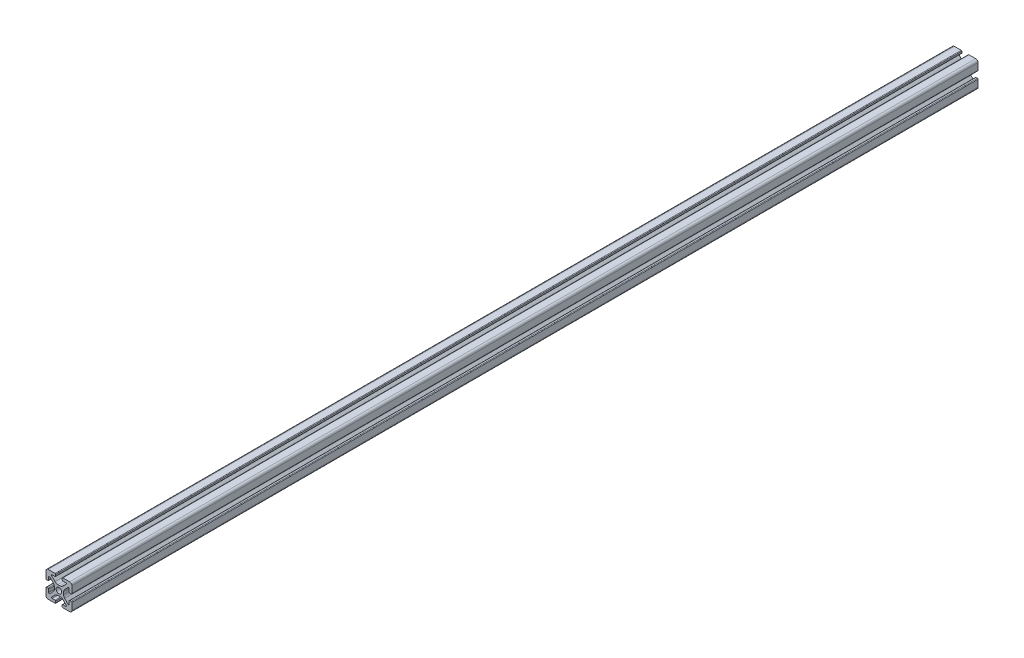
SolidWorks part; units mm, degrees
ref_plane "Front Plane" through (0, 0, 0) normal (0, 0, 1) x (1, 0, 0)
ref_plane "Top Plane" through (0, 0, 0) normal (0, 1, 0) x (1, 0, 0)
ref_plane "Right Plane" through (0, 0, 0) normal (1, 0, 0) x (0, 0, -1)
sketch "Sketch2" plane through (0, 0, 0) normal (0, 0, 1) x (1, 0, 0)
  line L0 (0, 10) -> (0, -10) construction
  line L1 (-10, 0) -> (10, 0) construction
  line L2 (2.5, -10) -> (10, -10)
  line L3 (10, -10) -> (10, -2.5)
  line L4 (2.5, -10) -> (2.5, -7.9246)
  line L5 (2.5, -7.9246) -> (6.4571, -7.9246)
  line L6 (6.4571, -7.9246) -> (2.1325, -3.6)
  line L7 (0, 0) -> (10, -10) construction
  line L8 (10, -2.5) -> (7.9246, -2.5)
  line L9 (7.9246, -2.5) -> (7.9246, -6.4571)
  line L10 (7.9246, -6.4571) -> (3.6, -2.1325)
  line L11 (5.7623, -4.2948) -> (4.2948, -5.7623) construction
  circle A0 centre (0, 0) radius 2.15
  arc A1 (5.25, -7.9246) -> (5.6036, -7.0711) centre (5.25, -7.4246) ccw construction
  point P8 (0, -3.6)
  point P16 (5.0286, -5.0286)
  dimension "Center Hole Diameter" = 4.3
  dimension "D3" = 0.5
  dimension "Rail Height" = 20
  dimension "Rail Width" = 20
  dimension "T-Slot Width" = 5
  dimension "Slot Depth" = 6.4
  dimension "Slot Inner Width" = 11.5
sketch "Sketch3" plane through (0, 0, 0) normal (1, 0, 0) x (0, 0, -1)
  line L0 (-76.2, -10) -> (76.2, -10) construction
  line L1 (-50.8, 0) -> (50.8, 0) construction
  line L2 (0, 10) -> (0, -10) construction
  line L3 (0, 10) -> (0, -10) construction
  point P6 (-50.8, 0)
  point P8 (50.8, 0)
  dimension "D1" = 25.4
  dimension "Length" = 152.4
sketch "Sketch4" plane through (0, 0, 0) normal (0, 0, 1) x (1, 0, 0)
  line L0 (3, -10) -> (8.25, -10)
  line L1 (2.5, -10) -> (10, -10) construction
  line L2 (2.5, -10) -> (2.5, -7.9246) construction
  line L3 (2.5, -7.9246) -> (6.4571, -7.9246) construction
  line L4 (2.5, -8.4246) -> (2.5, -9.5)
  line L5 (3, -7.9246) -> (5.25, -7.9246)
  line L6 (0, -3.6) -> (0.8898, -3.6)
  line L7 (6.4571, -7.9246) -> (2.1325, -3.6) construction
  line L8 (3.0112, -4.4787) -> (5.6036, -7.0711)
  line L9 (10, -10) -> (10, -2.5) construction
  line L10 (7.9246, -6.4571) -> (3.6, -2.1325) construction
  line L11 (7.9246, -2.5) -> (7.9246, -6.4571) construction
  line L12 (7.9246, -5.25) -> (7.9246, -3)
  line L13 (10, -2.5) -> (7.9246, -2.5) construction
  line L14 (8.4246, -2.5) -> (9.5, -2.5)
  line L15 (10, -3) -> (10, -8.25)
  line L16 (7.0711, -5.6036) -> (4.4787, -3.0112)
  line L17 (3.6, 0) -> (3.6, -0.8898)
  line L18 (-10, 0) -> (10, 0) construction
  line L19 (0, -3.6) -> (0, -2.15)
  line L20 (0, 10) -> (0, -10) construction
  line L21 (3.6, 0) -> (2.15, 0)
  arc A0 (2.5, -9.5) -> (3, -10) centre (3, -9.5) ccw
  arc A1 (5.25, -7.9246) -> (5.6036, -7.0711) centre (5.25, -7.4246) ccw construction
  arc A2 (2.5, -8.4246) -> (3, -7.9246) centre (3, -8.4246) cw
  arc A3 (5.25, -7.9246) -> (5.6036, -7.0711) centre (5.25, -7.4246) ccw
  arc A4 (0.8898, -3.6) -> (3.0112, -4.4787) centre (0.8898, -6.6) cw
  arc A5 (8.25, -10) -> (10, -8.25) centre (8.25, -8.25) ccw
  arc A6 (7.0711, -5.6036) -> (7.9246, -5.25) centre (7.4246, -5.25) ccw
  arc A7 (7.9246, -3) -> (8.4246, -2.5) centre (8.4246, -3) cw
  arc A8 (9.5, -2.5) -> (10, -3) centre (9.5, -3) cw
  arc A9 (4.4787, -3.0112) -> (3.6, -0.8898) centre (6.6, -0.8898) cw
  circle A10 centre (0, 0) radius 2.15 construction
  arc A11 (0, -2.15) -> (2.15, 0) centre (0, 0) ccw
  dimension "D1" = 1.75
  dimension "D2" = 3
extrude "Boss-Extrude1" add sketch "Sketch4" along normal mid plane 700
mirror "Mirror1" about plane through (0, 0, 0) normal (1, 0, 0) of bodies 134
mirror "Mirror2" about plane through (0, 0, 0) normal (0, 1, 0) of bodies 135
equation "\"D3@Sketch2\"=\"T-Slot Width@Sketch2\"*0.1"
equation "\"D1@Sketch4\"=\"D3@Sketch2\"*3.5"
equation "\"D2@Sketch4\"=\"D3@Sketch2\"*6"
equation "\"D1@Boss-Extrude1\"=110"
